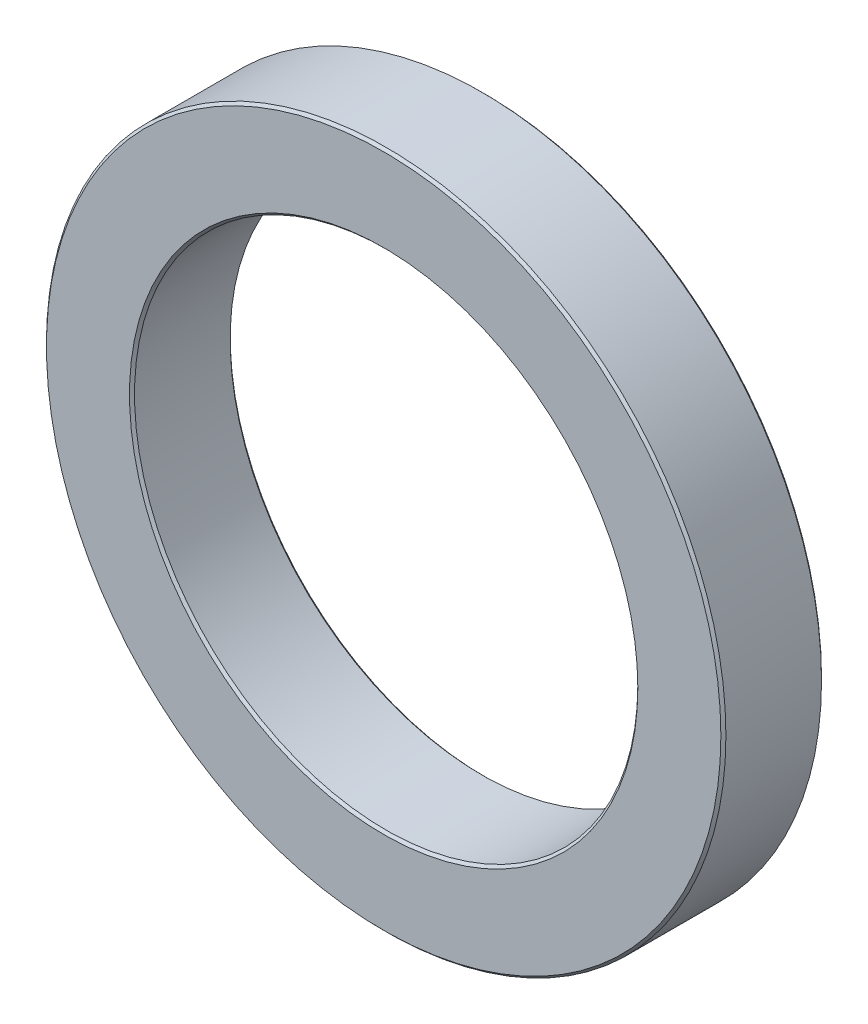
SolidWorks part; units mm, degrees
material "1023 碳钢板 (SS)"
ref_plane "前视基准面" through (0, 0, 0) normal (0, 0, 1) x (1, 0, 0)
ref_plane "上视基准面" through (0, 0, 0) normal (0, 1, 0) x (1, 0, 0)
ref_plane "右视基准面" through (0, 0, 0) normal (1, 0, 0) x (0, 0, -1)
other "Configuration Table"
sketch "草图1" plane through (0, 0, 0) normal (0, 0, 1) x (1, 0, 0)
  circle A0 centre (0, 0) radius 10
  circle A1 centre (0, 0) radius 13.5
  dimension "D1" = 20
  dimension "D2" = 27
extrude "凸台-拉伸1" add sketch "草图1" along normal blind 4
chamfer "倒角1" distance 0.1 angle 45 4 edges at (10, 0, 0) (10, 0, 4) (13.5, 0, 0) (13.5, 0, 4)
